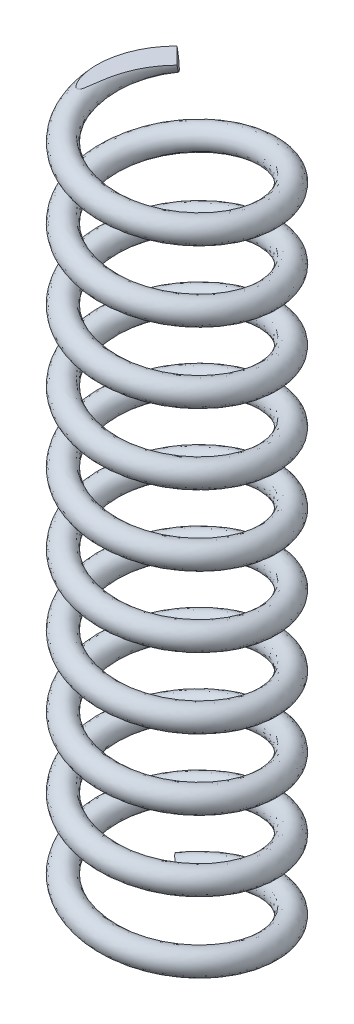
SolidWorks part; units mm, degrees
ref_plane "Front Plane" through (0, 0, 0) normal (0, 0, 1) x (1, 0, 0)
ref_plane "Top Plane" through (0, 0, 0) normal (0, 1, 0) x (1, 0, 0)
ref_plane "Right Plane" through (0, 0, 0) normal (1, 0, 0) x (0, 0, -1)
sketch "Sketch1" plane through (0, 0, 0) normal (0, 1, 0) x (1, 0, 0)
  circle A0 centre (0, 0) radius 2.75
  dimension "D1" = 5.5
curve "Helix/Spiral1" pitch 2.4 height 24 turns 10
sweep "Sweep1" add path "Helix/Spiral1" circular profile diameter 0.8 parameters "D3"=0.8
ref_plane "Plane1" through (0, 0, 0) normal (0, 1, 0) x (1, 0, 0)
sketch "Sketch21" plane through (0, 0, 0) normal (0, 1, 0) x (1, 0, 0)
  line L1 (2.9148, 3.4251) -> (-3.1854, 3.4251)
  line L2 (2.9148, 3.4251) -> (2.9148, -0.4704)
  line L3 (2.9148, -0.4704) -> (-3.1854, -0.4704)
  line L4 (-3.1854, 3.4251) -> (-3.1854, -0.4704)
extrude "Cut-Extrude1" cut sketch "Sketch21" against normal up to next
ref_plane "Plane2" through (0, 24, 0) normal (0, 1, 0) x (1, 0, 0)
sketch "Sketch22" plane through (0, 24, 0) normal (0, 1, 0) x (1, 0, 0)
  line L5 (-3.8398, 3.5068) -> (3.3704, 3.5068)
  line L6 (-3.8398, 3.5068) -> (-3.8398, -2.9988)
  line L7 (-3.8398, -2.9988) -> (3.3704, -2.9988)
  line L8 (3.3704, 3.5068) -> (3.3704, -2.9988)
extrude "Cut-Extrude2" cut sketch "Sketch22" along normal up to next
